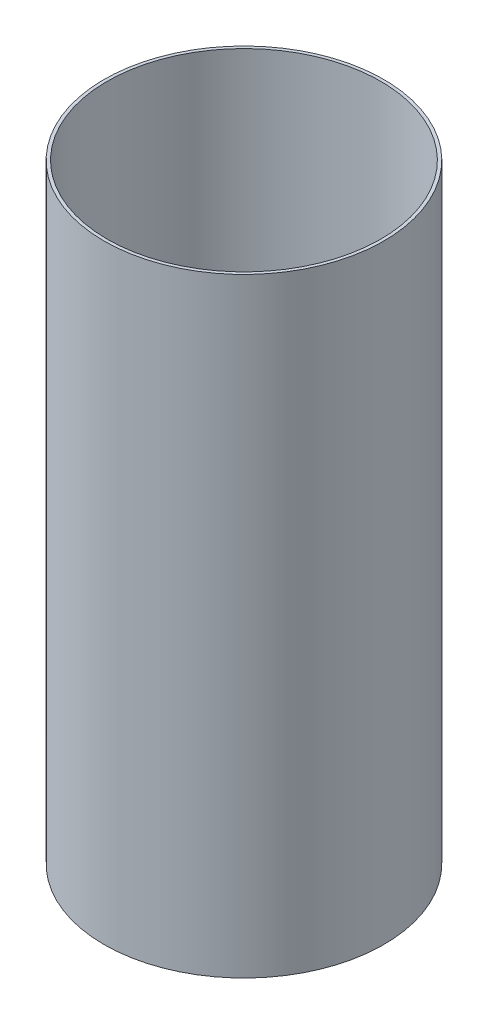
SolidWorks part; units mm, degrees
ref_plane "Front Plane" through (0, 0, 0) normal (0, 0, 1) x (1, 0, 0)
ref_plane "Top Plane" through (0, 0, 0) normal (0, 1, 0) x (1, 0, 0)
ref_plane "Right Plane" through (0, 0, 0) normal (1, 0, 0) x (0, 0, -1)
ref_plane "Plane1"
sketch "Sketch1" plane through (0, 0, 0) normal (0, 1, 0) x (-1, 0, 0)
  circle A0 centre (0, 0) radius 22.5
  circle A1 centre (0, 0) radius 22
  dimension "D1" = 45
  dimension "D2" = 44
extrude "Extrusion1" add sketch "Sketch1" along normal blind 98 contours A0 A1
